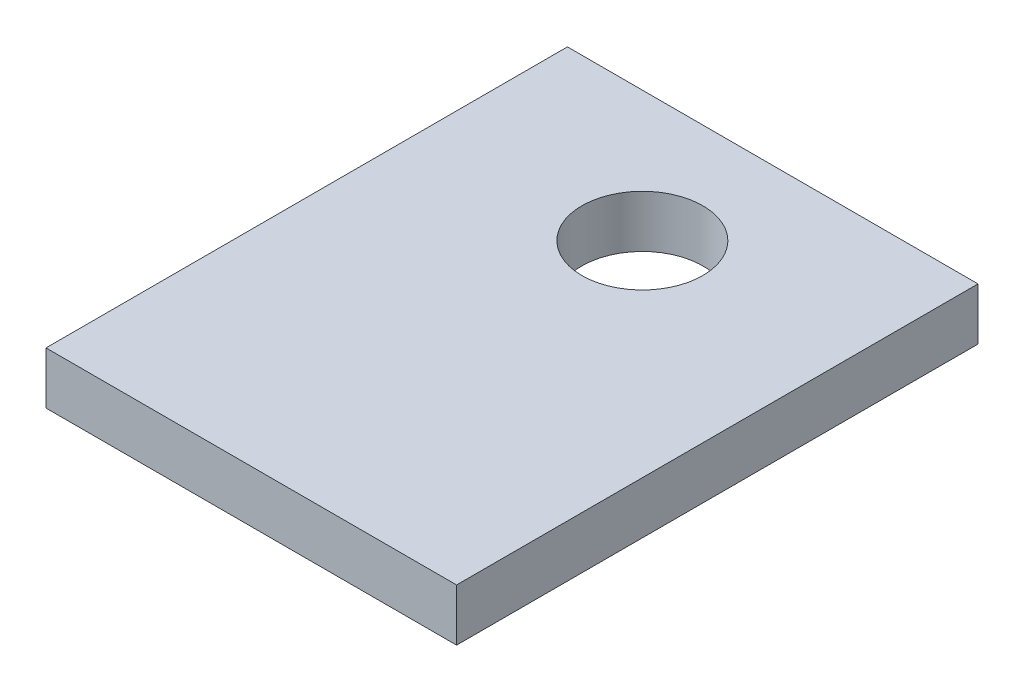
SolidWorks part; units mm, degrees
material "Copper"
ref_plane "Front Plane" through (0, 0, 0) normal (0, 0, 1) x (1, 0, 0)
ref_plane "Top Plane" through (0, 0, 0) normal (0, 1, 0) x (1, 0, 0)
ref_plane "Right Plane" through (0, 0, 0) normal (1, 0, 0) x (0, 0, -1)
sketch "Sketch1" plane through (0, 0, 0) normal (0, 1, 0) x (1, 0, 0)
  line L1 (0, 0) -> (10, 0)
  line L2 (0, 0) -> (0, -12.7)
  line L3 (0, -12.7) -> (10, -12.7)
  line L4 (10, 0) -> (10, -12.7)
  circle A0 centre (5, -3.175) radius 1.4732
  point P7 (0, 0)
  point P8 (5, 0)
  dimension "D2" = 2.9464
  dimension "D1" = 10
  dimension "D3" = 3.175
  dimension "D4" = 12.7
extrude "Boss-Extrude1" add sketch "Sketch1" along normal blind 1.27
